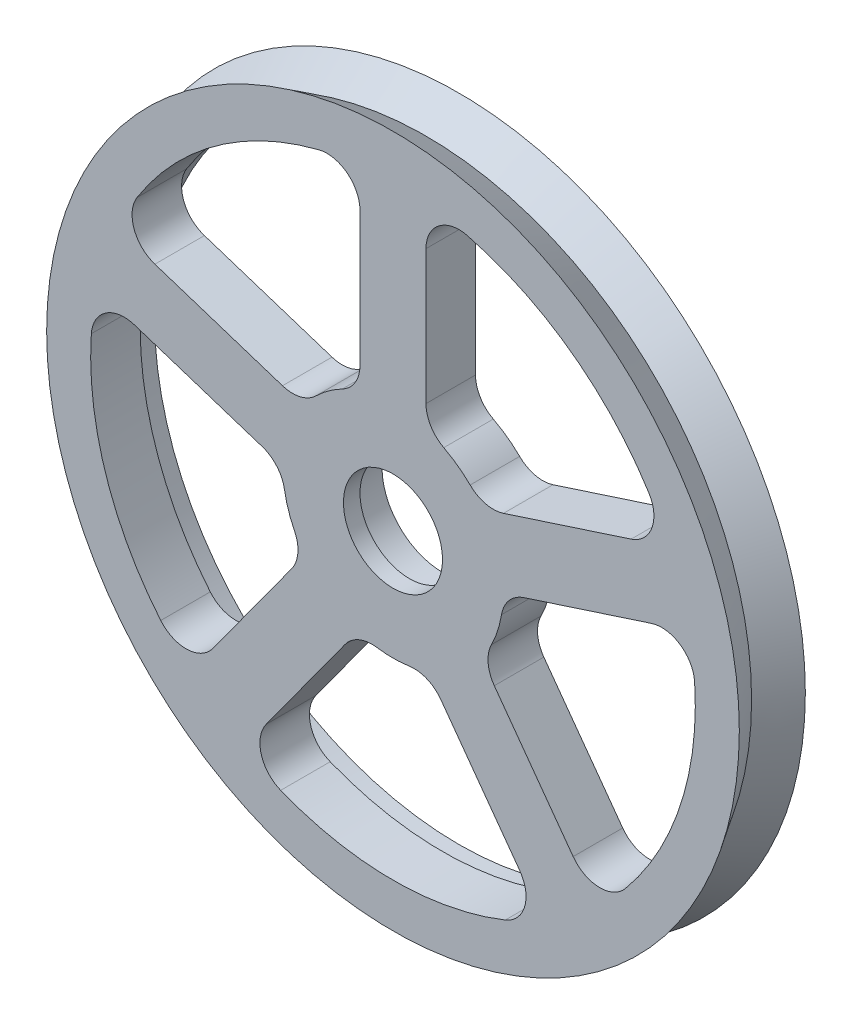
SolidWorks part; units mm, degrees
ref_plane "Front Plane" through (0, 0, 0) normal (0, 0, 1) x (1, 0, 0)
ref_plane "Top Plane" through (0, 0, 0) normal (0, 1, 0) x (1, 0, 0)
ref_plane "Right Plane" through (0, 0, 0) normal (1, 0, 0) x (0, 0, -1)
sketch "Sketch1" plane through (0, 0, 0) normal (1, 0, 0) x (0, 0, -1)
  line L0 (0, 0) -> (0, 31.4717) construction
  line L1 (2.5, 31.4717) -> (3, 31.4717) construction
  line L2 (3, 31.4717) -> (3, 4.5)
  line L3 (3, 4.5) -> (-3, 4.5)
  line L4 (-3, 31.4717) -> (-3, 4.5)
  line L5 (-2.5, 31.4717) -> (-3, 31.4717) construction
  line L6 (0, 0) -> (24.7394, 0) construction
  line L7 (-3, 31.4717) -> (0, 29.5872)
  line L8 (3, 31.4717) -> (0, 29.5872)
  circle A0 centre (0, 33.13) radius 3 construction
  point P9 (0, 4.5)
  point P13 (0, 30.13)
  dimension "D4" = 6
  dimension "D5" = 0.5
  dimension "D1" = 4.5
  dimension "D2" = 3
  dimension "D3" = 30.13
revolve "Revolve1" add sketch "Sketch1" angle 360 about L6
sketch "Sketch2" plane through (0, 0, 0) normal (0, 0, 1) x (1, 0, 0)
  line L0 (0, 0) -> (0, 60.5823) construction
  line L1 (-3, 27.3074) -> (-3, 9.5394)
  line L2 (3, 27.3074) -> (3, 9.5394)
  line L3 (25.0438, 11.2916) -> (8.1454, 5.801)
  line L4 (26.8979, 5.5853) -> (9.9996, 0.0947)
  line L5 (18.4779, -20.3288) -> (8.0342, -5.9542)
  line L6 (13.6238, -23.8555) -> (3.1801, -9.4809)
  line L7 (-13.6238, -23.8555) -> (-3.1801, -9.4809)
  line L8 (-18.4779, -20.3288) -> (-8.0342, -5.9542)
  line L9 (-26.8979, 5.5853) -> (-9.9996, 0.0947)
  line L10 (-25.0438, 11.2916) -> (-8.1454, 5.801)
  arc A0 (-3, 9.5394) -> (-8.1454, 5.801) centre (0, 0) ccw
  arc A1 (25.0438, 11.2916) -> (3, 27.3074) centre (0, 0) ccw
  arc A2 (-9.9996, 0.0947) -> (-8.0342, -5.9542) centre (0, 0) ccw
  arc A3 (8.1454, 5.801) -> (3, 9.5394) centre (0, 0) ccw
  arc A4 (8.0342, -5.9542) -> (9.9996, 0.0947) centre (0, 0) ccw
  arc A5 (-3.1801, -9.4809) -> (3.1801, -9.4809) centre (0, 0) ccw
  arc A6 (18.4779, -20.3288) -> (26.8979, 5.5853) centre (0, 0) ccw
  arc A7 (-13.6238, -23.8555) -> (13.6238, -23.8555) centre (0, 0) ccw
  arc A8 (-26.8979, 5.5853) -> (-18.4779, -20.3288) centre (0, 0) ccw
  arc A9 (-3, 27.3074) -> (-25.0438, 11.2916) centre (0, 0) ccw
  circle A10 centre (0, 0) radius 31.4717 construction
  point P27 (0, 0)
  dimension "D1" = 4
  dimension "D2" = 20
  dimension "D3" = 6
  dimension "D4" = 5
extrude "Cut-Extrude1" cut sketch "Sketch2" against normal mid plane 10
sketch "Sketch3" plane through (0, 0, -3) normal (0, 0, -1) x (-1, 0, 0)
  circle A0 centre (0, 0) radius 27.6717
extrude "Cut-Extrude2" cut sketch "Sketch3" against normal blind 1.5
fillet "Fillet1" radius 3 20 edges at (-26.8979, 5.5853, 0.75) (-18.4779, -20.3288, 0.75) (-25.0438, 11.2916, 0.75) (-8.0342, -5.9542, 0.75) (-3, 9.5394, 0.75) (-8.1454, 5.801, 0.75) (-3, 27.3074, 0.75) (-9.9996, 0.0947, 0.75) (-13.6238, -23.8555, 0.75) (13.6238, -23.8555, 0.75) (-3.1801, -9.4809, 0.75) (3.1801, -9.4809, 0.75) (18.4779, -20.3288, 0.75) (8.0342, -5.9542, 0.75) (9.9996, 0.0947, 0.75) (3, 27.3074, 0.75) (3, 9.5394, 0.75) (8.1454, 5.801, 0.75) (25.0438, 11.2916, 0.75) (26.8979, 5.5853, 0.75)
sketch "Sketch4" plane through (0, 0, 0) normal (0, 0, -1) x (-1, 0, 0)
  circle A0 centre (0, 0) radius 5.5
  dimension "D1" = 11
extrude "Cut-Extrude3" cut sketch "Sketch4" against normal blind 1.5 and the other way blind 11
sketch "Sketch5" plane through (0, 0, 0) normal (0, 0, 1) x (1, 0, 0)
  line L0 (3, 33.13) -> (15.8418, 24.9888)
  line L1 (0, 30.13) -> (0, 36.13) construction
  line L2 (-3, 33.13) -> (-15.8418, 24.9888)
  circle A1 centre (0, 33.13) radius 3 construction
  circle A2 centre (0, 0) radius 29.5872 construction
  dimension "D1" = 6
